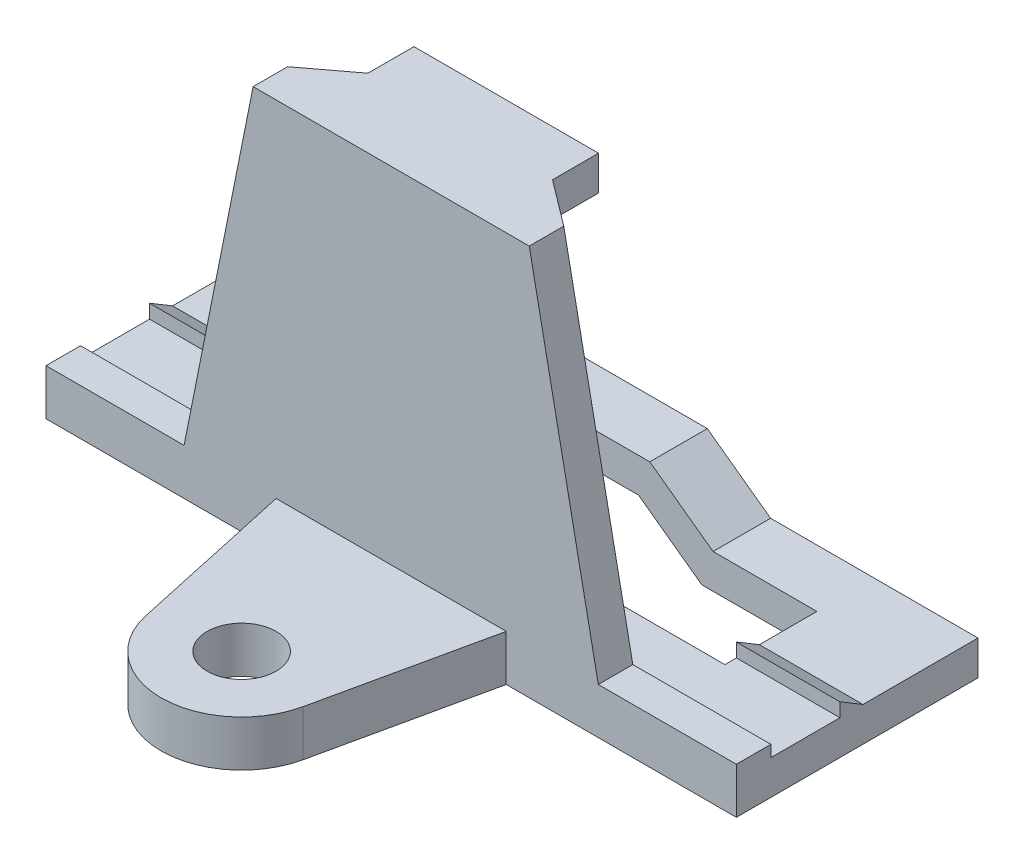
SolidWorks part; units mm, degrees
ref_plane "Alzado" through (0, 0, 0) normal (0, 0, 1) x (1, 0, 0)
ref_plane "Planta" through (0, 0, 0) normal (0, 1, 0) x (1, 0, 0)
ref_plane "Vista lateral" through (0, 0, 0) normal (1, 0, 0) x (0, 0, -1)
sketch "Croquis1" plane through (0, 0, 0) normal (0, 0, 1) x (1, 0, 0)
  line L0 (0, 8.5) -> (0, -8.5) construction
  line L1 (-6, 8.5) -> (6, 8.5)
  line L3 (-15, -8.5) -> (15, -8.5)
  line L4 (15, -6.5) -> (15, -8.5)
  line L5 (0, 0) -> (15, -8.5) construction
  line L6 (0, 0) -> (6.9162, 3.9192) construction
  line L7 (6, 8.5) -> (9, -6.5)
  line L8 (9, -6.5) -> (15, -6.5)
  line L9 (0, 0) -> (-6.9162, 3.9192) construction
  line L10 (0, 0) -> (-15, -8.5) construction
  line L11 (-9, -6.5) -> (-15, -6.5)
  line L12 (-6, 8.5) -> (-9, -6.5)
  line L13 (-15, -6.5) -> (-15, -8.5)
  point P0 (0, 0)
  point P10 (0, 0)
  dimension "D3" = 2
  dimension "D4" = 6
  dimension "D5" = 6
extrude "Saliente-Extruir1" add sketch "Croquis1" along normal blind 1.5
sketch "Croquis2" plane through (0, 0, 1.5) normal (0, 0, 1) x (1, 0, 0)
  line L0 (-15, -8.5) -> (15, -8.5) construction
  line L2 (-5, -8.5) -> (-5, -6.5)
  line L3 (-5, -6.5) -> (5, -6.5)
  line L4 (5, -8.5) -> (5, -6.5)
  line L5 (0, -8.5) -> (5, -6.5) construction
  line L6 (-5, -6.5) -> (0, -8.5) construction
  line L7 (-5, -8.5) -> (5, -8.5)
  line L8 (5, -7.9191) -> (15, -7.9191) construction
  line L9 (15, -8.5) -> (15, -6.5) construction
  line L10 (-5, -7.9191) -> (-15, -7.9191) construction
  line L11 (-15, -6.5) -> (-15, -8.5) construction
  point P0 (0, -8.5)
  dimension "D1" = 10
  dimension "D2" = 2
extrude "Saliente-Extruir2" add sketch "Croquis2" along normal blind 10
sketch "Croquis3" plane through (0, -8.5, 0) normal (0, -1, 0) x (1, 0, 0)
  line L0 (-5, 11.5) -> (5, 11.5) construction
  line L1 (-5, 1.5) -> (-3.4196, 8.7459)
  line L2 (3.4196, 8.7459) -> (5, 1.5)
  line L3 (5, 1.5) -> (5, 11.5)
  line L4 (5, 11.5) -> (-5, 11.5)
  line L5 (-5, 11.5) -> (-5, 1.5)
  circle A0 centre (0, 8) radius 1.5
  arc A1 (3.4196, 8.7459) -> (-3.4196, 8.7459) centre (0, 8) ccw
  circle A2 centre (0, 8) radius 3.5 construction
  line M4 (5, 1.5) -> (5, 11.5)
  line M5 (5, 11.5) -> (-5, 11.5)
  line M6 (-5, 11.5) -> (-5, 1.5)
  dimension "D1" = 3
  dimension "D3" = 0
  dimension "D2" = 2
extrude "Cortar-Extruir1" cut sketch "Croquis3" against normal blind 10 contours A1 L4 L1 M6 | A1 L2 M4 M5 | A0
sketch "Croquis4" plane through (0, 8.5, 0) normal (0, 1, 0) x (1, 0, 0)
  line L0 (0, 0) -> (0, -6.144) construction
  line L1 (6, 0) -> (-6, 0) construction
  line L9 (6, -0.75) -> (-6, -0.75) construction
  line L10 (6, -1.5) -> (6, 0) construction
  line L11 (-6, -1.5) -> (-6, 0) construction
  line L12 (6, 0) -> (4.0109, 1.5)
  line L13 (4.0109, 1.5) -> (4.0109, 3.5)
  line L14 (-6, 0) -> (6, 0)
  line L15 (-4.0109, 3.5) -> (4.0109, 3.5)
  line L16 (-4.0109, 1.5) -> (-4.0109, 3.5)
  line L17 (-6, 0) -> (-4.0109, 1.5)
  point P27 (0, 3.5)
extrude "Saliente-Extruir5" add sketch "Croquis4" against normal blind 1.5 contours L15 L13 L12 L14 L17 L16
sketch "Croquis6" plane through (0, 0, -3.5) normal (0, 0, -1) x (-1, 0, 0)
  line L0 (-4.0109, 7) -> (0, 4.5)
  line L1 (0, 4.5) -> (4.0109, 7)
  line L2 (4.0109, 7) -> (-4.0109, 7)
  line L3 (4.0109, 8.5) -> (-4.0109, 8.5) construction
  dimension "D1" = 4
extrude "Saliente-Extruir6" add sketch "Croquis6" against normal blind 1.5 contours L0 L1 L2
fillet "Redondeo2" radius 1 1 edges at (0, 4.5, -2.75)
sketch "Croquis7" plane through (0, 0, 0) normal (0, 0, -1) x (-1, 0, 0)
  line L1 (5.5, -8.5) -> (15, -8.5)
  line L5 (2.75, -6.5) -> (5.5, -8.5)
  line L6 (0, -8.5) -> (0, 8.5) construction
  line L7 (4.0109, 8.5) -> (-4.0109, 8.5) construction
  line L8 (2.75, -6.5) -> (-2.75, -6.5)
  line L9 (-2.75, -6.5) -> (-5.5, -8.5)
  line L10 (-5.5, -8.5) -> (-15, -8.5)
  line L11 (5.9878, -7) -> (15, -7)
  line L12 (3.2378, -5) -> (5.9878, -7)
  line L13 (3.2378, -5) -> (-3.2378, -5)
  line L14 (-3.2378, -5) -> (-5.9878, -7)
  line L15 (-5.9878, -7) -> (-15, -7)
  line L16 (15, -8.5) -> (15, -7)
  line L17 (-15, -8.5) -> (-15, -7)
  point P1 (0, -6.5)
  point P7 (5.5, -8.5)
  point P9 (2.75, -6.5)
  point P10 (2.75, -6.5)
  point P12 (0, -8.5)
  point P17 (0, 0)
  point P19 (0, 0)
  point P20 (0, 0)
  dimension "D1" = 1.5
  dimension "D2" = 5.5
  dimension "D3" = 2.75
extrude "Saliente-Extruir7" add sketch "Croquis7" along normal blind 9
sketch "Croquis8" plane through (0, -8.5, 0) normal (0, -1, 0) x (1, 0, 0)
  line L0 (10.5, -4.5) -> (15, -4.5) construction
  line L5 (-10.5, -6.5) -> (10.5, -6.5)
  line L6 (-10.5, -6.5) -> (-10.5, -2.5)
  line L7 (-10.5, -2.5) -> (10.5, -2.5)
  line L8 (10.5, -6.5) -> (10.5, -2.5)
  line L9 (15, 1.5) -> (15, -9) construction
  line L10 (15, -4.5) -> (10.5, -4.5) construction
  line L11 (-10.5, -4.5) -> (-15, -4.5) construction
  line L12 (-15, 1.5) -> (-15, -9) construction
  line L13 (15, -9) -> (5.5, -9) construction
  dimension "D1" = 4
  dimension "D2" = 21
  dimension "D3" = 2.5
extrude "Cortar-Extruir2" cut sketch "Croquis8" against normal up to next
sketch "Croquis9" plane through (15, 0, 0) normal (1, 0, 0) x (0, 0, -1)
  line L0 (3, -7) -> (3, -6.4)
  line L1 (9, -7) -> (0, -7) construction
  line L2 (3, -6.4) -> (4, -7)
  line L3 (4, -7) -> (3, -7)
  line L4 (0, -7) -> (0, -6.5) construction
  dimension "D1" = 0.6
  dimension "D2" = 1
  dimension "D3" = 3
extrude "Saliente-Extruir8" add sketch "Croquis9" against normal up to surface (4.5 mm away) up to face at (10.5, -7.75, -4.5)
sketch "Croquis10" plane through (-15, 0, 0) normal (-1, 0, 0) x (0, 0, 1)
  line L0 (-3, -6.4) -> (-3, -7)
  line L1 (-9, -7) -> (0, -7) construction
  line L2 (-3, -7) -> (-3, -6.4) construction
  line L3 (-3, -7) -> (-4, -7)
  line L4 (-4, -7) -> (-3, -6.4)
extrude "Saliente-Extruir9" add sketch "Croquis10" against normal up to surface (4.5 mm away) up to face at (-10.5, -7.75, -4.5)
